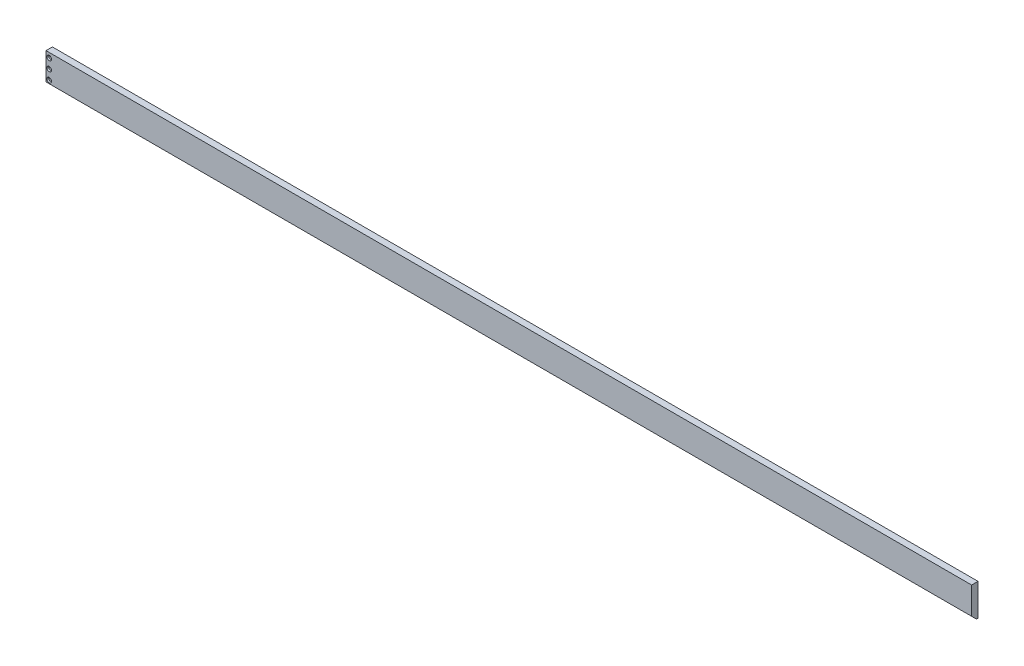
SolidWorks part; units mm, degrees
ref_plane "Ön Düzlem" through (0, 0, 0) normal (0, 0, 1) x (1, 0, 0)
ref_plane "Üst Düzlem" through (0, 0, 0) normal (0, 1, 0) x (1, 0, 0)
ref_plane "Sağ Düzlem" through (0, 0, 0) normal (1, 0, 0) x (0, 0, -1)
sketch "Çizim1" plane through (0, 0, 0) normal (0, 0, 1) x (1, 0, 0)
  line L1 (-1450, 50) -> (1450, 50)
  line L2 (-1450, 50) -> (-1450, -50)
  line L3 (-1450, -50) -> (1450, -50)
  line L4 (1450, 50) -> (1450, -50)
  line L5 (-1450, 50) -> (1450, -50) construction
  line L6 (-1450, -50) -> (1450, 50) construction
  point P0 (0, 0)
  dimension "D1" = 2900
  dimension "D2" = 100
extrude "Yükseklik-Ekstrüzyon1" add sketch "Çizim1" along normal blind 20
chamfer "Pah1" distance 15 angle 45 1 edges at (0, -50, 20)
sketch "Çizim2" plane through (0, 0, 20) normal (0, 0, 1) x (1, 0, 0)
  line L1 (1450, 50) -> (-1450, 50) construction
  line L2 (-1450, 50) -> (-1450, -35) construction
  circle A2 centre (-60, -5) radius 4.25
  circle A3 centre (-60, 25) radius 4.25
  circle A4 centre (-1205, 25) radius 4.25
  circle A5 centre (-1205, -5) radius 4.25
  circle A6 centre (980, 25) radius 4.25
  circle A7 centre (980, -5) radius 4.25
  dimension "D1" = 25
  dimension "D2" = 8.5
  dimension "D3" = 30
  dimension "D4" = 245
  dimension "D5" = 1390
  dimension "D6" = 1040
extrude "Kes-Ekstrüzyon1" [suppressed] cut sketch "Çizim2" against normal blind 85
sketch "Çizim3" plane through (0, 0, 20) normal (0, 0, 1) x (1, 0, 0)
  line L0 (-1450, 50) -> (-1450, -35) construction
  line L1 (1450, 50) -> (-1450, 50) construction
  circle A0 centre (-1440, 35) radius 4.25
  circle A1 centre (-1440, -25) radius 4.25
  circle A2 centre (-1440, 5) radius 4.25
  dimension "D1" = 8.5
  dimension "D2" = 10
  dimension "D3" = 15
  dimension "D4" = 30
  dimension "D5" = 30
extrude "Kes-Ekstrüzyon3" cut sketch "Çizim3" against normal blind 30
chamfer "Pah3" distance 3 angle 45 3 edges at (-1435.75, -25, 20) (-1435.75, 5, 20) (-1435.75, 35, 20)
chamfer "Pah4" [suppressed] distance 3 angle 45
